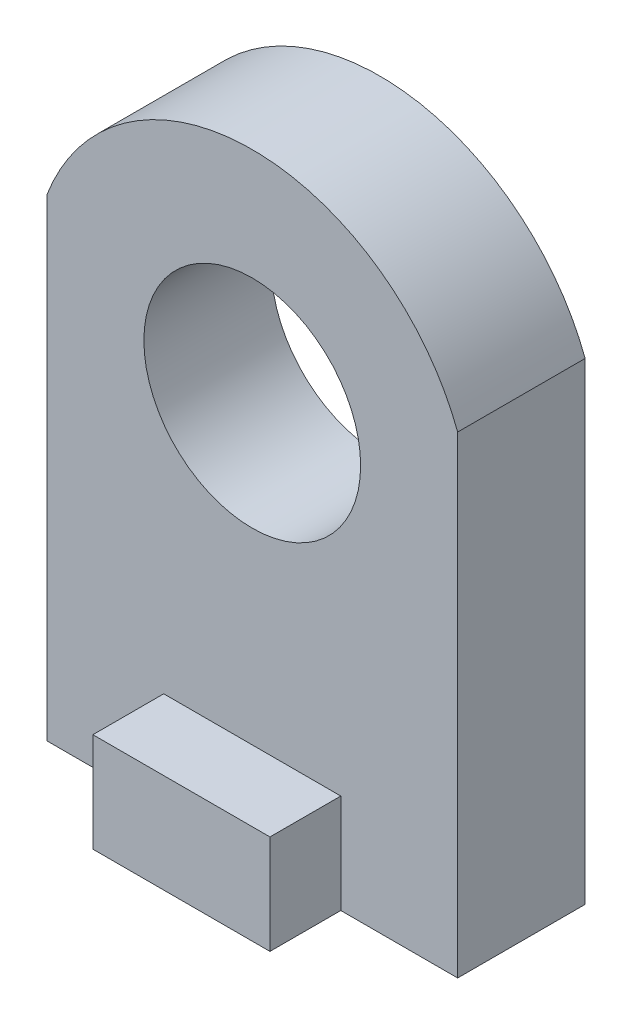
SolidWorks part; units mm, degrees
ref_plane "Front Plane" through (0, 0, 0) normal (0, 0, 1) x (1, 0, 0)
ref_plane "Top Plane" through (0, 0, 0) normal (0, 1, 0) x (1, 0, 0)
ref_plane "Right Plane" through (0, 0, 0) normal (1, 0, 0) x (0, 0, -1)
sketch "Sketch1" plane through (0, 0, 0) normal (0, 0, 1) x (1, 0, 0)
  line L0 (-14.5, -16.6886) -> (14.5, -16.6886)
  line L1 (-14.5, -16.6886) -> (-14.5, 16.6886)
  line L2 (14.5, -16.6886) -> (14.5, 16.6886)
  line L4 (-14.5, -16.6886) -> (14.5, 16.6886) construction
  line L5 (14.5, -16.6886) -> (-14.5, 16.6886) construction
  arc A0 (-14.5, 16.6886) -> (14.5, 16.6886) centre (0, 11.2114) cw
  circle A1 centre (0, 11.2114) radius 7.65
  point P1 (0, 0)
  point P3 (0, 26.7114)
  dimension "D2" = 15.5
  dimension "D4" = 15.3
  dimension "D1" = 29
  dimension "D3" = 43.4
extrude "Boss-Extrude1" add sketch "Sketch1" along normal blind 9
sketch "Sketch2" plane through (0, 0, 9) normal (0, 0, 1) x (1, 0, 0)
  line L0 (-14.5, -16.6886) -> (14.5, -16.6886) construction
  line L1 (-6.25, -16.6886) -> (6.25, -16.6886)
  line L2 (-6.25, -16.6886) -> (-6.25, -9.6886)
  line L3 (-6.25, -9.6886) -> (6.25, -9.6886)
  line L4 (6.25, -16.6886) -> (6.25, -9.6886)
  line L5 (0, 3.5614) -> (0, -16.6886) construction
  circle A0 centre (0, 11.2114) radius 7.65 construction
  point P11 (0, -16.6886)
  dimension "D1" = 12.5
  dimension "D2" = 7
extrude "Boss-Extrude2" add sketch "Sketch2" along normal blind 5
